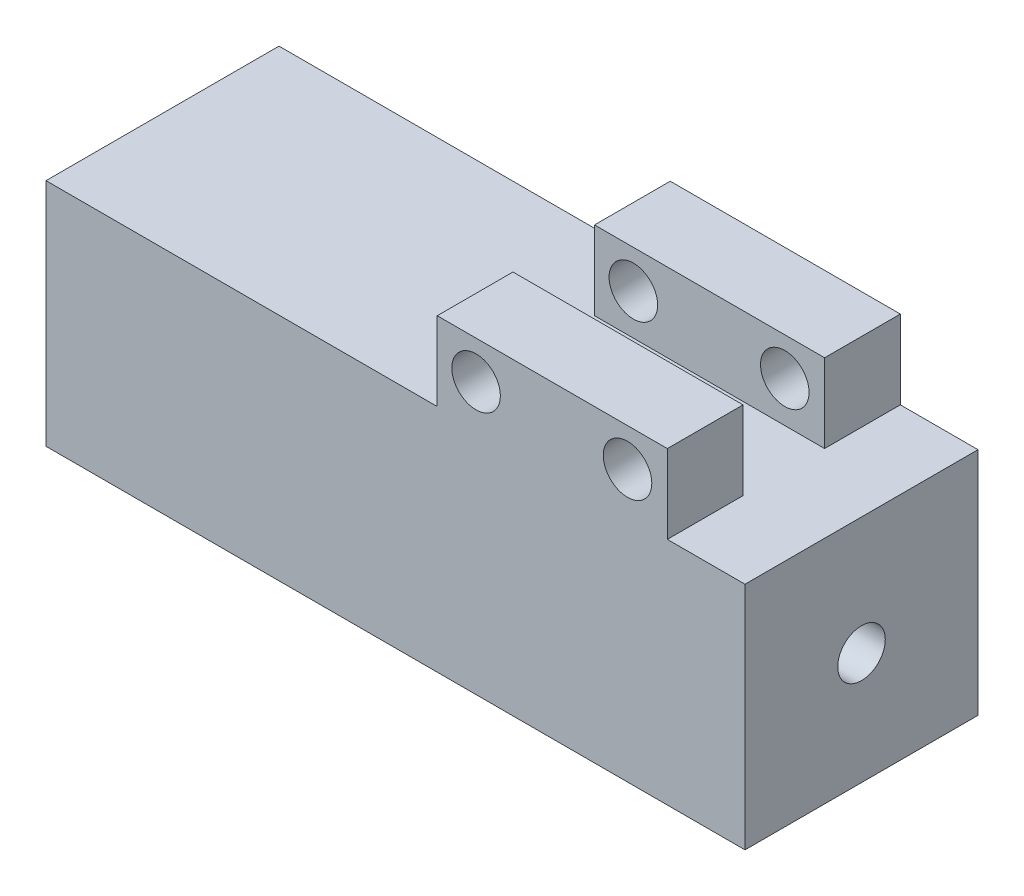
SolidWorks part; units mm, degrees
ref_plane "Front Plane" through (0, 0, 0) normal (0, 0, 1) x (1, 0, 0)
ref_plane "Top Plane" through (0, 0, 0) normal (0, 1, 0) x (1, 0, 0)
ref_plane "Right Plane" through (0, 0, 0) normal (1, 0, 0) x (0, 0, -1)
sketch "Sketch1" plane through (0, 0, 0) normal (0, 0, 1) x (1, 0, 0)
  line L1 (-36, -11.85) -> (36, -11.85)
  line L2 (-36, -11.85) -> (-36, 11.85)
  line L3 (-36, 11.85) -> (36, 11.85)
  line L4 (36, -11.85) -> (36, 11.85)
  line L5 (-36, -11.85) -> (36, 11.85) construction
  line L6 (-36, 11.85) -> (36, -11.85) construction
  point P4 (0, 0)
  point P5 (0, 0)
  dimension "D1" = 72
  dimension "D2" = 23.7
extrude "Boss-Extrude1" add sketch "Sketch1" along normal mid plane 24
sketch "Sketch2" plane through (36, 0, 0) normal (1, 0, 0) x (0, 0, -1)
  line L0 (0, -11.85) -> (0, -2.75) construction
  line L1 (-12, -11.85) -> (12, -11.85) construction
  line L2 (0, 13.035) -> (0, -13.035) construction
  circle A0 centre (0, -0.3) radius 2.45
  dimension "D2" = 4.9
  dimension "D1" = 9.1
sketch "Sketch3" plane through (0, 11.85, 0) normal (0, 1, 0) x (1, 0, 0)
  line L0 (36, -12) -> (-36, -12) construction
  line L1 (4.3, -12) -> (28, -12)
  line L2 (4.3, -12) -> (4.3, -4.2)
  line L3 (4.3, -4.2) -> (28, -4.2)
  line L4 (28, -12) -> (28, -4.2)
  line L5 (4.3, -12) -> (28, -4.2) construction
  line L6 (4.3, -4.2) -> (28, -12) construction
  line L7 (36, -12) -> (36, 12) construction
  line L8 (-13.035, 0) -> (13.035, 0) construction
  line L9 (4.3, 4.2) -> (28, 12) construction
  line L10 (4.3, 12) -> (28, 4.2) construction
  line L11 (28, 12) -> (28, 4.2)
  line L12 (4.3, 4.2) -> (28, 4.2)
  line L13 (4.3, 12) -> (4.3, 4.2)
  line L14 (4.3, 12) -> (28, 12)
  point P4 (16.15, -8.1)
  point P15 (16.15, 8.1)
  dimension "D1" = 8
  dimension "D2" = 23.7
  dimension "D3" = 7.8
extrude "Boss-Extrude2" add sketch "Sketch3" along normal blind 8.1
extrude "Cut-Extrude1" cut sketch "Sketch2" against normal blind 60
sketch "Sketch4" plane through (0, 0, 0) normal (0, 0, 1) x (1, 0, 0)
  line L0 (36, 11.85) -> (23.9, 11.85) construction
  line L1 (23.9, 11.85) -> (23.9, 16.05) construction
  line L2 (36, 11.85) -> (8.3, 11.85) construction
  line L6 (8.3, 11.85) -> (8.3, 16.05) construction
  circle A0 centre (8.3, 16.05) radius 2.5
  circle A1 centre (23.9, 16.05) radius 2.5
  dimension "D5" = 5
  dimension "D6" = 5
  dimension "D1" = 12.1
  dimension "D2" = 4.2
  dimension "D3" = 27.7
  dimension "D4" = 4.2
extrude "Cut-Extrude2" cut sketch "Sketch4" against normal through all both and the other way through all
equation "\"D1@Boss-Extrude2\"=31.8-23.7"
